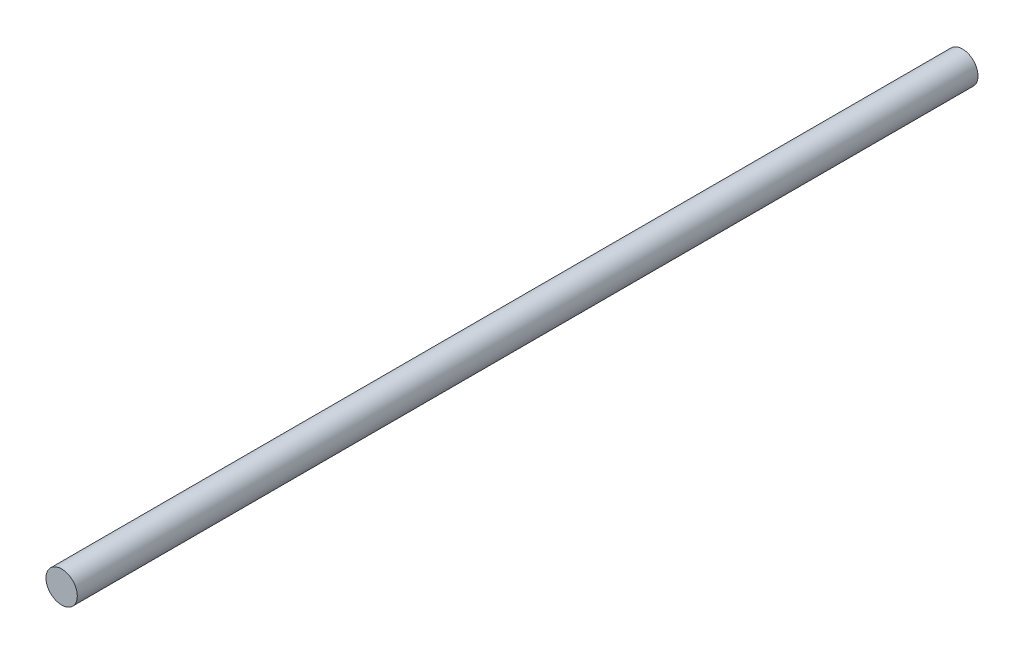
SolidWorks part; units mm, degrees
ref_plane "Front" through (0, 0, 0) normal (0, 0, 1) x (1, 0, 0)
ref_plane "Top" through (0, 0, 0) normal (0, 1, 0) x (1, 0, 0)
ref_plane "Right" through (0, 0, 0) normal (1, 0, 0) x (0, 0, -1)
sketch "Sketch1" plane through (0, 0, 0) normal (0, 0, 1) x (1, 0, 0)
  circle A0 centre (0, 0) radius 4
  dimension "D1" = 8
extrude "Boss-Extrude1" add sketch "Sketch1" along normal blind 230
equation "\"baseplate-height\"= 360mm"
equation "\"material-thickness\"= 9mm"
equation "\"linear-thread-dia\"= 8mm ' Diameter of the metal threaded rod used on the X Axis"
equation "\"nut_depth\"= 4.76mm"
equation "\"stepper_clearance\"= 29mm"
equation "\"rod_length_xaxis\"= \"baseplate-height\" - ( \"material-thickness\" + 20 ) + ( \"nut_depth\" * 2 ) + \"stepper_clearance\""
equation "\"D1@Sketch1\"=\"linear-thread-dia\""
